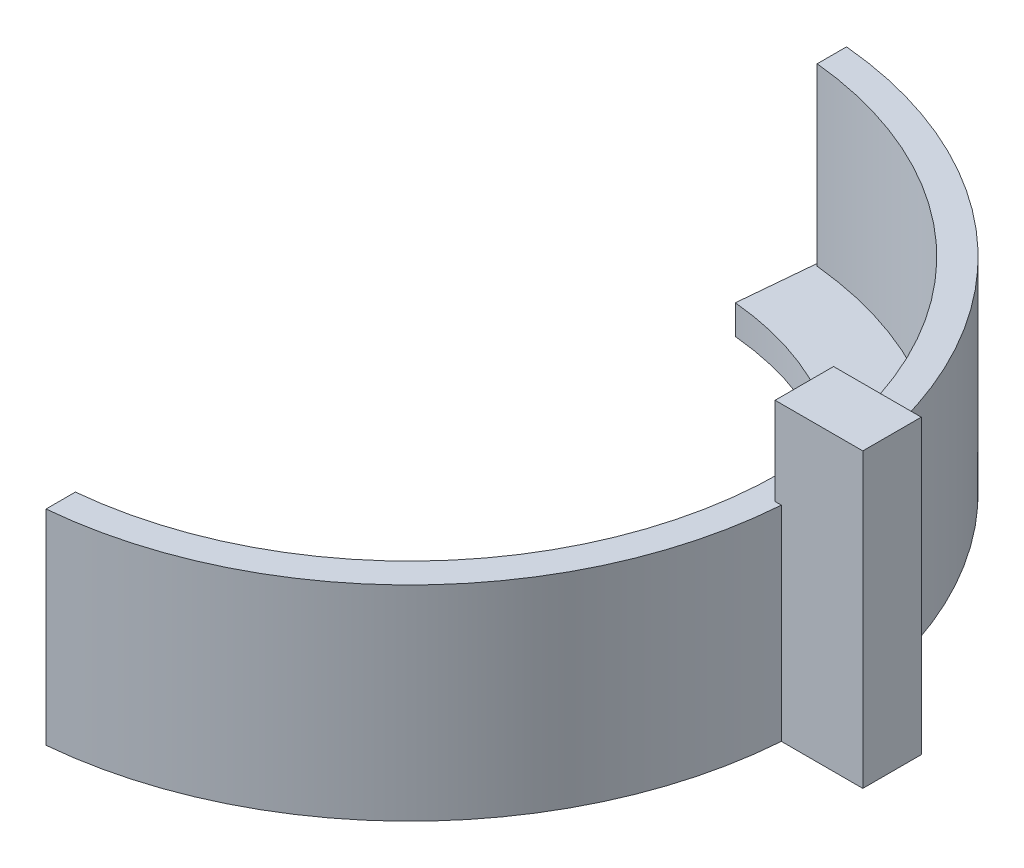
SolidWorks part; units mm, degrees
ref_plane "Front Plane" through (0, 0, 0) normal (0, 0, 1) x (1, 0, 0)
ref_plane "Top Plane" through (0, 0, 0) normal (0, 1, 0) x (1, 0, 0)
ref_plane "Right Plane" through (0, 0, 0) normal (1, 0, 0) x (0, 0, -1)
sketch "Sketch1" plane through (0, 0, 0) normal (0, 1, 0) x (1, 0, 0)
  line L4 (2.5, 27.3861) -> (2.5, 25.3772)
  line L6 (-2.5, 0) -> (2.5, 0) construction
  line L7 (2.5, -25.3772) -> (2.5, -27.3861)
  arc A2 (2.5, -27.3861) -> (2.5, 27.3861) centre (0, 0) ccw
  arc A5 (2.5, -25.3772) -> (2.5, 25.3772) centre (0, 0) ccw
  point P4 (24.3858, 7.4555)
  point P12 (26.2984, 8.0402)
extrude "Boss-Extrude1" add sketch "Sketch1" along normal blind 12
sketch "Sketch2" plane through (0, 0, 0) normal (0, 1, 0) x (1, 0, 0)
  line L0 (2.5, 27.3861) -> (1.8636, 20.4151)
  line L1 (2.5, -27.3861) -> (1.8636, -20.4151)
  arc A0 (2.5, 27.3861) -> (2.5, -27.3861) centre (0, 0) cw
  arc A1 (1.8636, 20.4151) -> (1.8636, -20.4151) centre (0, 0) cw
  dimension "D1" = 7
extrude "Boss-Extrude2" add sketch "Sketch2" against normal blind 2
sketch "Sketch4" plane through (0, -2, 0) normal (0, 1, 0) x (1, 0, 0)
  line L1 (27, 2) -> (33, 2)
  line L2 (27, 2) -> (27, -2)
  line L3 (27, -2) -> (33, -2)
  line L4 (33, 2) -> (33, -2)
  line L5 (30, -2) -> (30, 2) construction
  line L6 (27, 0) -> (33, 0) construction
  point P0 (30, 0)
  dimension "D1" = 6
  dimension "D2" = 4
  dimension "D3" = 30
extrude "Boss-Extrude3" add sketch "Sketch4" along normal blind 20
